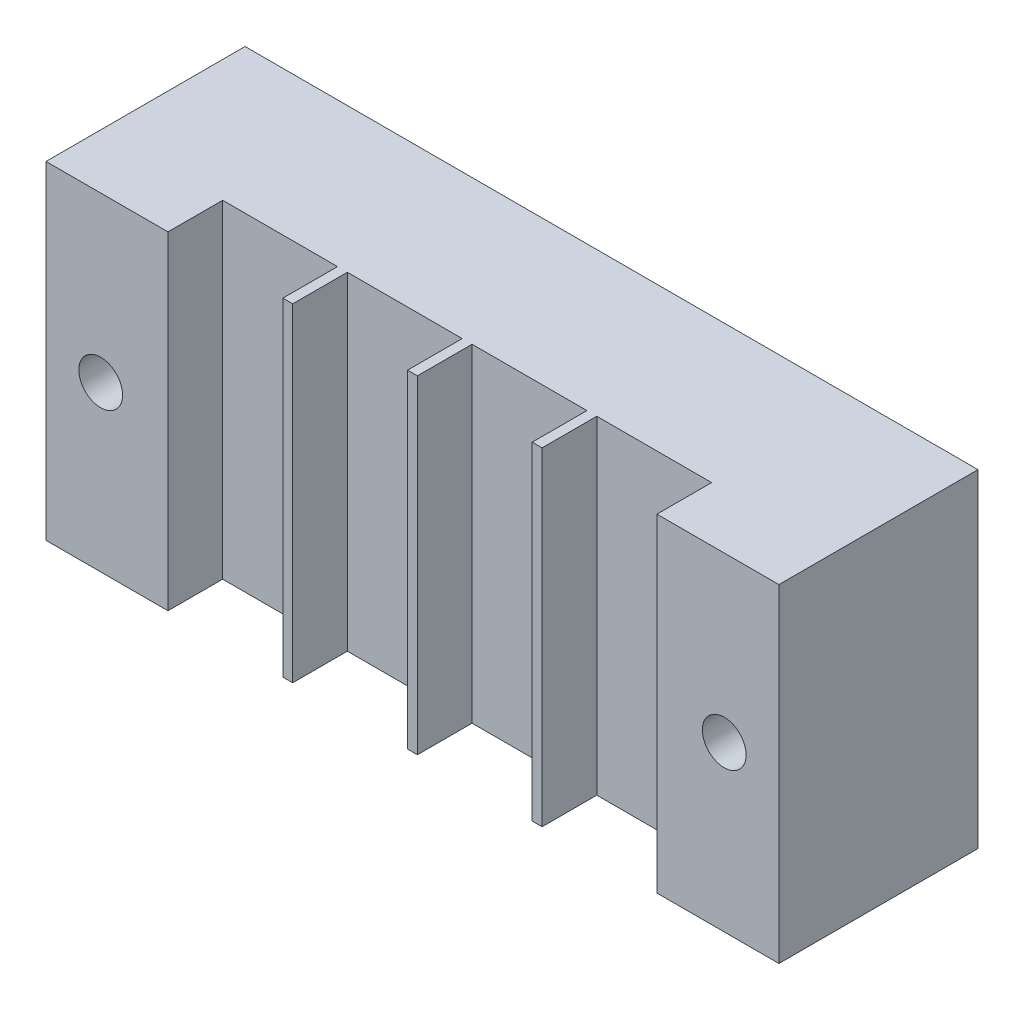
SolidWorks part; units mm, degrees
ref_plane "前视基准面" through (0, 0, 0) normal (0, 0, 1) x (1, 0, 0)
ref_plane "上视基准面" through (0, 0, 0) normal (0, 1, 0) x (1, 0, 0)
ref_plane "右视基准面" through (0, 0, 0) normal (1, 0, 0) x (0, 0, -1)
sketch "草图1" plane through (0, 0, 0) normal (0, 0, 1) x (1, 0, 0)
  line L0 (-74.6184, 0) -> (60.9357, 0) construction
  line L1 (-33.5, 15) -> (33.5, 15)
  line L2 (-33.5, 15) -> (-33.5, -15)
  line L3 (-33.5, -15) -> (33.5, -15)
  line L4 (33.5, 15) -> (33.5, -15)
  line L5 (0, 35.1613) -> (0, -34.5249) construction
  dimension "D1" = 67
  dimension "D2" = 30
extrude "凸台-拉伸1" add sketch "草图1" along normal blind 18.2
sketch "草图2" plane through (0, 0, 18.2) normal (0, 0, 1) x (1, 0, 0)
  line L0 (-55.5688, 0) -> (51.5182, 0) construction
  line L1 (0, 29.4932) -> (0, -23.9237) construction
  circle A0 centre (-28.5, 0) radius 2
  circle A1 centre (28.5, 0) radius 2
  dimension "D1" = 4
  dimension "D2" = 57
extrude "切除-拉伸1" cut sketch "草图2" against normal blind 19
sketch "草图3" plane through (0, 0, 18.2) normal (0, 0, 1) x (1, 0, 0)
  line L0 (33.5, 15) -> (-33.5, 15) construction
  line L1 (-0.45, 15) -> (-10.95, 15)
  line L2 (-0.45, 15) -> (-0.45, -15)
  line L3 (-0.45, -15) -> (-10.95, -15)
  line L4 (-10.95, 15) -> (-10.95, -15)
  line L5 (-33.5, -15) -> (33.5, -15) construction
  line L6 (0, -23.8247) -> (0, 34.5354) construction
  line L7 (-11.85, 15) -> (-22.35, 15)
  line L8 (-11.85, 15) -> (-11.85, -15)
  line L9 (-11.85, -15) -> (-22.35, -15)
  line L10 (-22.35, 15) -> (-22.35, -15)
  line L11 (22.35, 15) -> (22.35, -15)
  line L12 (11.85, -15) -> (22.35, -15)
  line L13 (11.85, 15) -> (11.85, -15)
  line L14 (11.85, 15) -> (22.35, 15)
  line L15 (10.95, 15) -> (10.95, -15)
  line L16 (0.45, -15) -> (10.95, -15)
  line L17 (0.45, 15) -> (0.45, -15)
  line L18 (0.45, 15) -> (10.95, 15)
  dimension "D1" = 10.5
  dimension "D3" = 0.9
  dimension "D2" = 2
extrude "切除-拉伸2" cut sketch "草图3" against normal blind 5
